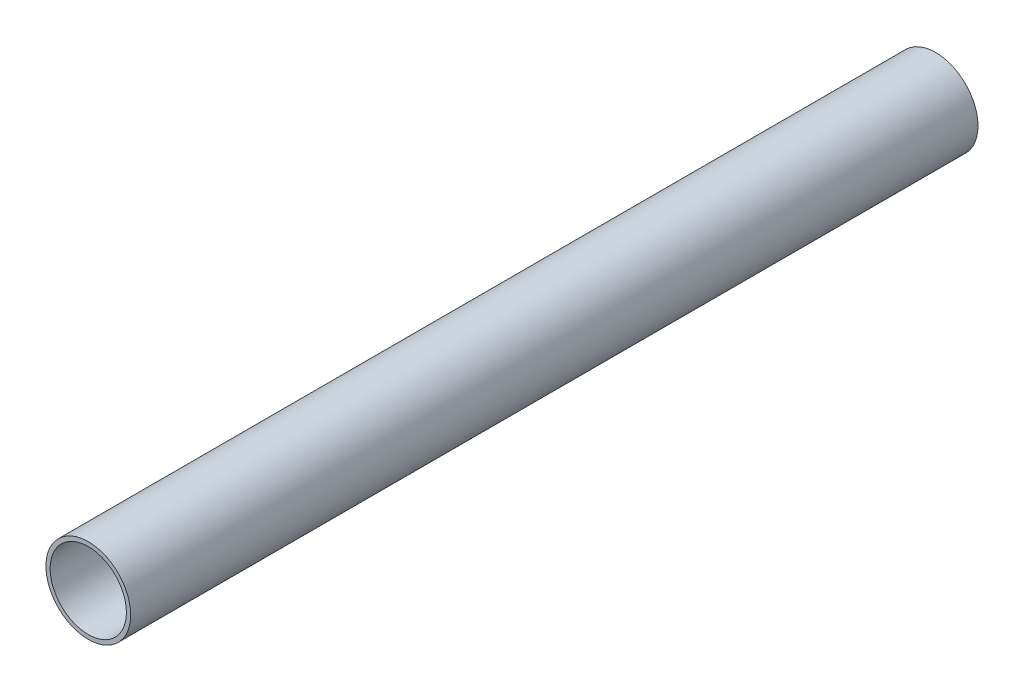
SolidWorks part; units mm, degrees
ref_plane "Front Plane" through (0, 0, 0) normal (0, 0, 1) x (1, 0, 0)
ref_plane "Top Plane" through (0, 0, 0) normal (0, 1, 0) x (1, 0, 0)
ref_plane "Right Plane" through (0, 0, 0) normal (1, 0, 0) x (0, 0, -1)
sketch "Sketch1" plane through (0, 0, 0) normal (0, 0, 1) x (1, 0, 0)
  circle A0 centre (0, 0) radius 15
  circle A1 centre (0, 0) radius 13.5
  dimension "D1" = 30
  dimension "D2" = 27
extrude "Boss-Extrude1" add sketch "Sketch1" along normal blind 300
